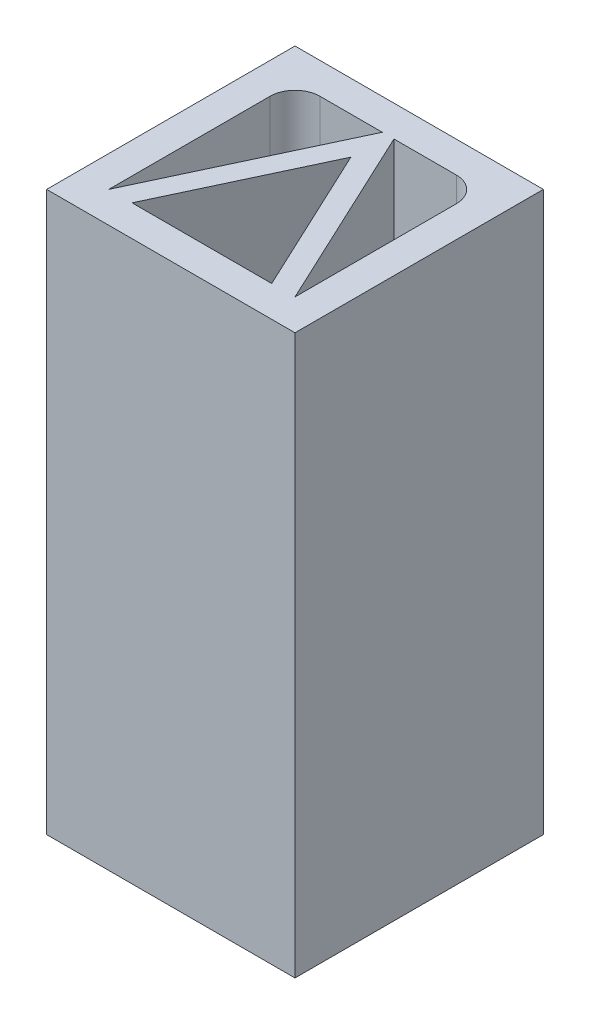
SolidWorks part; units mm, degrees
ref_plane "Front Plane" through (0, 0, 0) normal (0, 0, 1) x (1, 0, 0)
ref_plane "Top Plane" through (0, 0, 0) normal (0, 1, 0) x (1, 0, 0)
ref_plane "Right Plane" through (0, 0, 0) normal (1, 0, 0) x (0, 0, -1)
sketch "Sketch1" plane through (0, 0, 0) normal (0, 1, 0) x (1, 0, 0)
  line L0 (10, 20) -> (10, 17.5) construction
  line L1 (0, 0) -> (20, 0)
  line L2 (0, 0) -> (0, 20)
  line L3 (0, 20) -> (20, 20)
  line L4 (20, 0) -> (20, 20)
  line L5 (2.5, 17.5) -> (17.5, 17.5)
  line L6 (2.5, 17.5) -> (2.5, 2.5)
  line L7 (2.5, 2.5) -> (17.5, 2.5)
  line L8 (17.5, 17.5) -> (17.5, 2.5)
  line L9 (0, 10) -> (2.5, 10) construction
  dimension "D1" = 20
  dimension "D2" = 20
  dimension "D3" = 2.5
  dimension "D4" = 2.5
extrude "Boss-Extrude1" add sketch "Sketch1" along normal blind 45
sketch "Sketch3" plane through (0, 0, 0) normal (0, -1, 0) x (1, 0, 0)
  line L0 (17.5, -2.5) -> (10, -18.5)
  line L2 (10, -18.5) -> (2.5, -2.5)
  line L3 (10, -18.5) -> (10, -2.5) construction
  line L4 (2.5, -2.5) -> (17.5, -2.5) construction
  line L5 (17.5, -2.5) -> (15.625, -2.5)
  line L6 (15.625, -2.5) -> (10, -14.5)
  line L7 (10, -14.5) -> (4.375, -2.5)
  line L8 (4.375, -2.5) -> (2.5, -2.5)
  line L9 (17.5, -17.5) -> (2.5, -17.5) construction
  point P3 (12.5, -23.5225)
  point P13 (0, 0)
  dimension "D1" = 4
  dimension "D2" = 1
extrude "Boss-Extrude4" add sketch "Sketch3" against normal through all
fillet "Fillet2" radius 2 2 edges at (2.5, 22.5, -17.5) (17.5, 22.5, -17.5)
